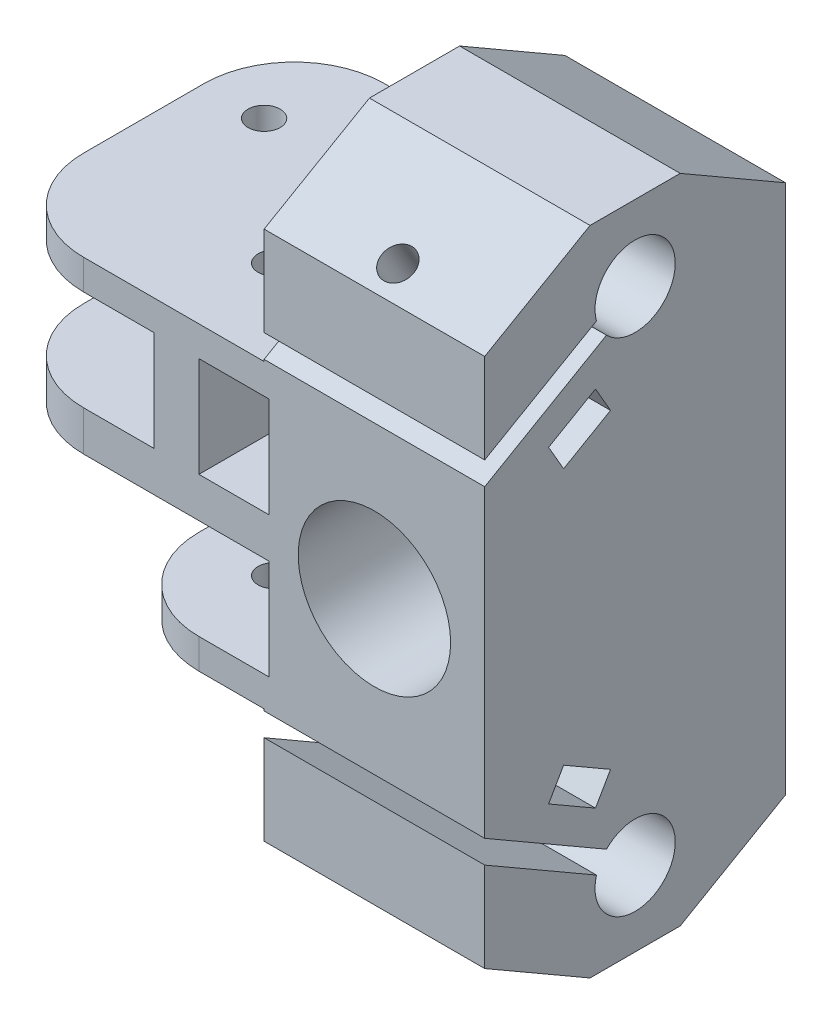
SolidWorks part; units mm, degrees
ref_plane "Plano frontal" through (0, 0, 0) normal (0, 0, 1) x (1, 0, 0)
ref_plane "Plano superior" through (0, 0, 0) normal (0, 1, 0) x (1, 0, 0)
ref_plane "Plano direito" through (0, 0, 0) normal (1, 0, 0) x (0, 0, -1)
sketch "Esboço2" plane through (0, 0, 0) normal (0, 0, 1) x (1, 0, 0)
  line L0 (-11, 15) -> (-11, 32.5)
  line L1 (-11, -32.5) -> (11, -32.5)
  line L2 (-11, -32.5) -> (-11, -15)
  line L3 (-11, 32.5) -> (11, 32.5)
  line L4 (11, -32.5) -> (11, 32.5)
  line L5 (-11, -32.5) -> (11, 32.5) construction
  line L6 (-11, 32.5) -> (11, -32.5) construction
  line L7 (-38, 15) -> (-11, 15)
  line L8 (-38, 15) -> (-38, 12)
  line L9 (-26.5, -15) -> (-11, -15)
  line L10 (0, 0) -> (-50.7474, 0) construction
  line L11 (-38, 15) -> (-11, -15) construction
  line L12 (-38, -15) -> (-11, 15) construction
  line L13 (-17.5, 2) -> (-10.5, 2)
  line L14 (-17.5, 2) -> (-17.5, 12)
  line L15 (-17.5, 12) -> (-10.5, 12)
  line L16 (-10.5, 2) -> (-10.5, 12)
  line L17 (-17.5, 2) -> (-10.5, 12) construction
  line L18 (-17.5, 12) -> (-10.5, 2) construction
  line L19 (-22, 12) -> (-38, 12)
  line L20 (-22, 12) -> (-22, 2)
  line L21 (-22, 2) -> (-38, 2)
  line L22 (-38, -2) -> (-26.5, -2)
  line L23 (-22, 12) -> (-38, 2) construction
  line L24 (-22, 2) -> (-38, 12) construction
  line L25 (-10.5, -2) -> (-26.5, -2)
  line L26 (-10.5, -2) -> (-10.5, -12)
  line L27 (-10.5, -12) -> (-26.5, -12)
  line L29 (-26.5, -12) -> (-26.5, -15)
  line L31 (-38, 2) -> (-38, -2)
  line L33 (-10.5, -2) -> (-26.5, -12) construction
  line L34 (-10.5, -12) -> (-26.5, -2) construction
  circle A0 centre (0, 0) radius 7.6
  point P7 (-24.5, 0)
  point P12 (-14, 7)
  point P18 (-30, 7)
  point P26 (-18.5, -7)
  dimension "D1" = 15.2
  dimension "D2" = 65
  dimension "D3" = 22
  dimension "D4" = 30
  dimension "D5" = 27
  dimension "D6" = 3
  dimension "D7" = 7
  dimension "D9" = 16
  dimension "D10" = 0.5
  dimension "D11" = 10
  dimension "D12" = 3
extrude "Ressalto-extrusão1" add sketch "Esboço2" along normal blind 30
sketch "Esboço3" plane through (-11, 0, 0) normal (-1, 0, 0) x (0, 0, 1)
  line L0 (0, 0) -> (30, 0) construction
  line L1 (30, 15) -> (0, 15) construction
  line L2 (30, 26.4348) -> (19.4948, 32.5)
  line L3 (30, 32.5) -> (30, 15) construction
  line L4 (15, 32.5) -> (15, 15) construction
  line L5 (18.9522, 18.0994) -> (23.6287, 15.3994)
  line L6 (18.9522, 18.0994) -> (17.4522, 15.5013)
  line L7 (17.4522, 15.5013) -> (22.1287, 12.8013)
  line L8 (23.6287, 15.3994) -> (22.1287, 12.8013)
  line L9 (18.9522, 18.0994) -> (22.1287, 12.8013) construction
  line L10 (17.4522, 15.5013) -> (23.6287, 15.3994) construction
  line L12 (18.3535, 23.0639) -> (31.633, 15.3969) construction
  line L13 (17.8541, 22.1975) -> (31.133, 14.5309)
  line L14 (18.8541, 23.9295) -> (32.133, 16.2629)
  line L15 (15.5, 25.866) -> (32.133, 16.2629) construction
  line L16 (15, 25) -> (31.633, 15.3969) construction
  line L17 (14.5, 24.134) -> (31.133, 14.5309) construction
  line L18 (31.133, 14.5309) -> (32.133, 16.2629)
  line L19 (18.3535, -23.0639) -> (31.633, -15.3969) construction
  line L20 (17.4522, -15.5013) -> (23.6287, -15.3994) construction
  line L21 (18.9522, -18.0994) -> (22.1287, -12.8013) construction
  line L22 (31.133, -14.5309) -> (32.133, -16.2629)
  line L23 (18.8541, -23.9295) -> (32.133, -16.2629)
  line L24 (17.8541, -22.1975) -> (31.133, -14.5309)
  line L25 (23.6287, -15.3994) -> (22.1287, -12.8013)
  line L26 (17.4522, -15.5013) -> (22.1287, -12.8013)
  line L27 (18.9522, -18.0994) -> (17.4522, -15.5013)
  line L28 (18.9522, -18.0994) -> (23.6287, -15.3994)
  line L29 (30, 32.5) -> (0, 32.5) construction
  line L30 (30, 15) -> (0, 15) construction
  line L31 (0, 26.4348) -> (10.5052, 32.5)
  line L32 (0, 26.4348) -> (0, 32.5)
  line L33 (0, 32.5) -> (10.5052, 32.5)
  line L34 (30, 26.4348) -> (30, 32.5)
  line L35 (30, 32.5) -> (19.4948, 32.5)
  line L36 (30, -32.5) -> (19.4948, -32.5)
  line L37 (30, -26.4348) -> (30, -32.5)
  line L38 (0, -32.5) -> (10.5052, -32.5)
  line L39 (0, -26.4348) -> (0, -32.5)
  line L40 (0, -26.4348) -> (10.5052, -32.5)
  line L41 (30, -26.4348) -> (19.4948, -32.5)
  arc A0 (18.8541, 23.9295) -> (17.8541, 22.1975) centre (15, 25) ccw
  arc A1 (18.8541, -23.9295) -> (17.8541, -22.1975) centre (15, -25) cw
  point P11 (20.5404, 15.4504)
  point P33 (20.5404, -15.4504)
  point P37 (15, 32.5)
  dimension "D1" = 4
  dimension "D2" = 50
  dimension "D3" = 5.4
  dimension "D4" = 3
  dimension "D5" = 3
  dimension "D8" = 30
  dimension "D9" = 3
  dimension "D6" = 1
  dimension "D7" = 1
extrude "Corte-extrusão1" cut sketch "Esboço3" against normal through all
sketch "Esboço4" plane through (0, 15, 0) normal (0, 1, 0) x (1, 0, 0)
  line L1 (11, -15) -> (-38, -15) construction
  line L2 (11, -19.4948) -> (11, -10.5052) construction
  line L5 (-38, -30) -> (-38, 0) construction
  line L6 (-32, -9) -> (-32, -15) construction
  line L7 (-11, 0) -> (-38, 0) construction
  line L8 (-19, -21) -> (-19, -15) construction
  circle A0 centre (-32, -9) radius 1.6
  circle A1 centre (-32, -9) radius 5 construction
  circle A2 centre (-32, -9) radius 7 construction
  circle A3 centre (-19, -21) radius 1.6
  circle A4 centre (-19, -21) radius 5 construction
  dimension "D2" = 14
  dimension "D3" = 2
  dimension "D1" = 3.2
  dimension "D5" = 10
  dimension "D4" = 32
  dimension "D6" = 19
extrude "Corte-extrusão2" cut sketch "Esboço4" against normal through all both and the other way through all
fillet "Filete2" radius 9 6 edges at (-38, 13.5, 30) (-26.5, -13.5, 0) (-38, 0, 0) (-38, 13.5, 0) (-38, 0, 30) (-26.5, -13.5, 30)
sketch "Esboço7" plane through (0, 19.183, 11.0753) normal (0, 0.866, 0.5) x (1, 0, 0)
  line L0 (11, -7.3634) -> (-11, -7.3634) construction
  line L1 (11, -7.3634) -> (11, -12.7634) construction
  circle A0 centre (0, -10.0634) radius 1.6
  point P4 (0, -7.3634)
  point P7 (11, -10.0634)
  dimension "D1" = 3.2
extrude "Corte-extrusão3" cut sketch "Esboço7" against normal blind 10 and the other way through all
